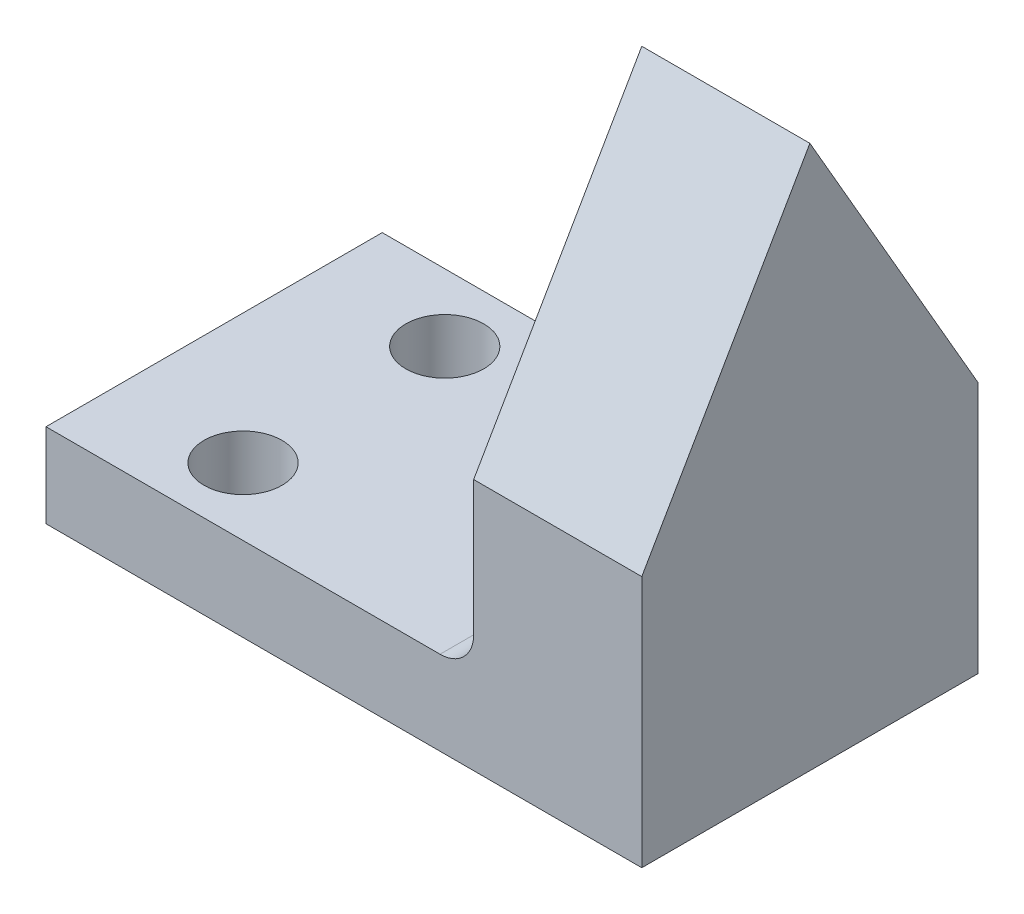
SolidWorks part; units mm, degrees
material "6061-T6 (SS)"
ref_plane "Front Plane" through (0, 0, 0) normal (0, 0, 1) x (1, 0, 0)
ref_plane "Top Plane" through (0, 0, 0) normal (0, 1, 0) x (1, 0, 0)
ref_plane "Right Plane" through (0, 0, 0) normal (1, 0, 0) x (0, 0, -1)
sketch "Sketch1" plane through (0, 0, 0) normal (0, 1, 0) x (1, 0, 0)
  line L0 (-9.6647, 0) -> (-9.6647, 3.81) construction
  line L1 (-7.9375, -6.35) -> (7.9375, -6.35)
  line L2 (-7.9375, -6.35) -> (-7.9375, 6.35)
  line L3 (-7.9375, 6.35) -> (7.9375, 6.35)
  line L4 (7.9375, -6.35) -> (7.9375, 6.35)
  line L5 (-7.9375, -6.35) -> (7.9375, 6.35) construction
  line L6 (-7.9375, 6.35) -> (7.9375, -6.35) construction
  line L7 (-7.9375, 6.35) -> (-11.3919, 6.35)
  line L8 (-7.9375, 6.35) -> (-7.9375, -6.35)
  line L9 (-7.9375, -6.35) -> (-11.3919, -6.35)
  line L10 (-11.3919, 6.35) -> (-11.3919, -6.35)
  line L11 (-9.6647, 0) -> (-9.6647, -3.81) construction
  line L12 (-8.1915, 3.81) -> (-8.1915, -3.3338) construction
  line L13 (-9.6647, 0) -> (-11.3919, 0) construction
  circle A0 centre (-9.6647, 3.81) radius 1.4732
  circle A1 centre (-9.6647, -3.81) radius 1.4732
  point P0 (0, 0)
  dimension "D3" = 2.9464
  dimension "D4" = 2.9464
  dimension "D1" = 15.875
  dimension "D2" = 12.7
  dimension "D5" = 16.129
  dimension "D6" = 3.81
  dimension "D7" = 3.81
extrude "Boss-Extrude1" add sketch "Sketch1" along normal blind 3.175 contours L7 L10 L9 L2 A1 A0 | L1 L4 L3 L2
sketch "Sketch2" plane through (7.9375, 0, 0) normal (1, 0, 0) x (0, 0, -1)
  line L0 (6.35, 3.175) -> (6.35, 0) construction
  line L1 (-6.35, 3.175) -> (6.35, 3.175)
  line L2 (-6.35, 3.175) -> (-6.35, 9.525)
  line L3 (-6.35, 9.525) -> (6.35, 9.525)
  line L4 (6.35, 3.175) -> (6.35, 9.525)
  line L5 (-6.35, 9.525) -> (0, 20.5235)
  line L6 (0, 20.5235) -> (6.35, 9.525)
  line M3 (6.35, 3.175) -> (-6.35, 3.175)
  dimension "D1" = 6.35
  dimension "D2" = 60
  dimension "D3" = 60
extrude "Boss-Extrude2" add sketch "Sketch2" against normal blind 6.35 contours L4 L3 L2 M3 | L6 L5 L3
sketch "Sketch3" plane through (-11.3919, 0, 0) normal (-1, 0, 0) x (0, 0, 1)
  line L4 (-6.35, 0) -> (6.35, 0)
  line L5 (6.35, 0) -> (6.35, 3.175)
  line L6 (6.35, 3.175) -> (-6.35, 3.175)
  line L7 (-6.35, 3.175) -> (-6.35, 0)
  line L8 (-6.35, 0) -> (6.35, 0)
  line L9 (6.35, 0) -> (6.35, 3.175)
  line L10 (6.35, 3.175) -> (-6.35, 3.175)
  line L11 (-6.35, 3.175) -> (-6.35, 0)
  dimension "D1" = 0
extrude "Boss-Extrude3" add sketch "Sketch3" along normal blind 3.175
fillet "Fillet1" radius 1.27 1 edges
